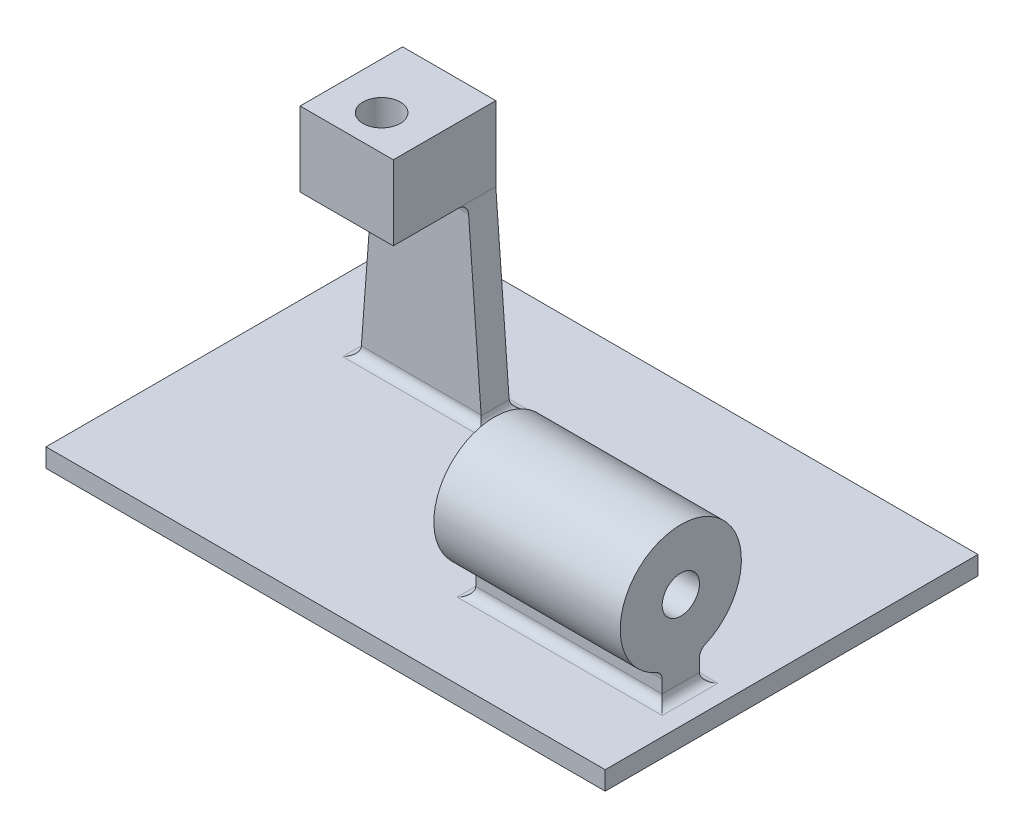
SolidWorks part; units mm, degrees
ref_plane "Front Plane" through (0, 0, 0) normal (0, 0, 1) x (1, 0, 0)
ref_plane "Top Plane" through (0, 0, 0) normal (0, 1, 0) x (1, 0, 0)
ref_plane "Right Plane" through (0, 0, 0) normal (1, 0, 0) x (0, 0, -1)
sketch "Sketch1" plane through (0, 0, 0) normal (0, 1, 0) x (1, 0, 0)
  line L1 (-30, -20) -> (30, -20)
  line L2 (-30, -20) -> (-30, 20)
  line L3 (-30, 20) -> (30, 20)
  line L4 (30, -20) -> (30, 20)
  line L5 (-30, -20) -> (30, 20) construction
  line L6 (-30, 20) -> (30, -20) construction
  point P0 (0, 0)
  dimension "D1" = 60
  dimension "D2" = 40
extrude "Boss-Extrude1" add sketch "Sketch1" along normal blind 2
sketch "Sketch2" plane through (0, 2, 0) normal (0, 1, 0) x (1, 0, 0)
  line L1 (-21.5406, 5.3036) -> (-8.5406, 5.3036)
  line L2 (-21.5406, 5.3036) -> (-21.5406, 8.3036)
  line L3 (-21.5406, 8.3036) -> (-8.5406, 8.3036)
  line L4 (-8.5406, 5.3036) -> (-8.5406, 8.3036)
  line L5 (-21.5406, 5.3036) -> (-8.5406, 8.3036) construction
  line L6 (-21.5406, 8.3036) -> (-8.5406, 5.3036) construction
  point P0 (-15.0406, 6.8036)
  dimension "D1" = 13
  dimension "D2" = 3
ref_plane "Plane1" through (0, 22, 0) normal (0, 1, 0) x (1, 0, 0)
sketch "Sketch3" plane through (0, 22, 0) normal (0, 1, 0) x (1, 0, 0)
  line L0 (-21.5406, 8.3036) -> (-8.5406, 8.3036) construction
  line L1 (-20.0406, 5.3036) -> (-10.0406, 5.3036)
  line L2 (-20.0406, 5.3036) -> (-20.0406, 8.3036)
  line L3 (-20.0406, 8.3036) -> (-10.0406, 8.3036)
  line L4 (-10.0406, 5.3036) -> (-10.0406, 8.3036)
  line L5 (-20.0406, 5.3036) -> (-10.0406, 8.3036) construction
  line L6 (-20.0406, 8.3036) -> (-10.0406, 5.3036) construction
  point P0 (-15.0406, 6.8036)
  dimension "D1" = 10
loft "Loft1" add profiles "Sketch3", "Sketch2"
sketch "Sketch4" plane through (0, 22, 0) normal (0, 1, 0) x (1, 0, 0)
  line L0 (-10.0406, 5.3036) -> (-10.0406, 8.3036) construction
  line L1 (-20.0406, 5.3036) -> (-10.0406, 5.3036)
  line L2 (-20.0406, 5.3036) -> (-20.0406, 8.3036)
  line L3 (-20.0406, 8.3036) -> (-10.0406, 8.3036)
  line L4 (-10.0406, 5.3036) -> (-10.0406, 8.3036)
  line L5 (-20.0406, 5.3036) -> (-10.0406, 8.3036) construction
  line L6 (-20.0406, 8.3036) -> (-10.0406, 5.3036) construction
  line L7 (-10.0406, 8.3036) -> (-20.0406, 8.3036) construction
  point P0 (-15.0406, 6.8036)
extrude "Boss-Extrude2" add sketch "Sketch4" along normal blind 8
sketch "Sketch6" plane through (0, 0, -5.3036) normal (0, 0, 1) x (1, 0, 0)
  line L5 (-20.0406, 17) -> (-10.0406, 30) construction
  line L6 (-20.0406, 30) -> (-10.0406, 17) construction
  line L7 (-20.0406, 22) -> (-10.0406, 22)
  line L8 (-20.0406, 22) -> (-20.0406, 30)
  line L9 (-20.0406, 30) -> (-10.0406, 30)
  line L10 (-10.0406, 22) -> (-10.0406, 30)
  line L11 (-20.0406, 22) -> (-10.0406, 30) construction
  line L12 (-20.0406, 30) -> (-10.0406, 22) construction
  point P0 (-15.0406, 23.5)
  point P6 (-15.0406, 26)
extrude "Boss-Extrude5" add sketch "Sketch6" along normal blind 8 contours L9 L10 L7 L8
sketch "Sketch8" plane through (0, 30, 0) normal (0, 1, 0) x (1, 0, 0)
  circle A0 centre (-15.0406, 1.0488) radius 2
  dimension "D1" = 4
extrude "Cut-Extrude2" cut sketch "Sketch8" against normal blind 8
sketch "Sketch9" plane through (0, 2, 0) normal (0, 1, 0) x (1, 0, 0)
  line L1 (7.0196, -10.9075) -> (27.0196, -10.9075)
  line L2 (7.0196, -10.9075) -> (7.0196, -6.9075)
  line L3 (7.0196, -6.9075) -> (27.0196, -6.9075)
  line L4 (27.0196, -10.9075) -> (27.0196, -6.9075)
  line L5 (7.0196, -10.9075) -> (27.0196, -6.9075) construction
  line L6 (7.0196, -6.9075) -> (27.0196, -10.9075) construction
  point P0 (17.0196, -8.9075)
  dimension "D1" = 20
  dimension "D2" = 4
extrude "Boss-Extrude6" add sketch "Sketch9" along normal blind 4 contours L3 L4 L1 L2
sketch "Sketch10" plane through (27.0196, 0, 0) normal (1, 0, 0) x (0, 0, -1)
  circle A0 centre (-8.9075, 11.238) radius 6.5
  circle A1 centre (-8.9075, 11.238) radius 2
  dimension "D1" = 13
  dimension "D2" = 4
extrude "Boss-Extrude7" add sketch "Sketch10" against normal blind 20
fillet "Fillet1" radius 1 4 edges
fillet "Fillet2" radius 1 1 edges
fillet "Fillet3" radius 1 6 edges at (17.0196, 5.0534, 6.9075) (7.0196, 2, 8.9075) (17.0196, 5.0534, 10.9075) (17.0196, 2, 10.9075) (27.0196, 2, 8.9075) (17.0196, 2, 6.9075)
